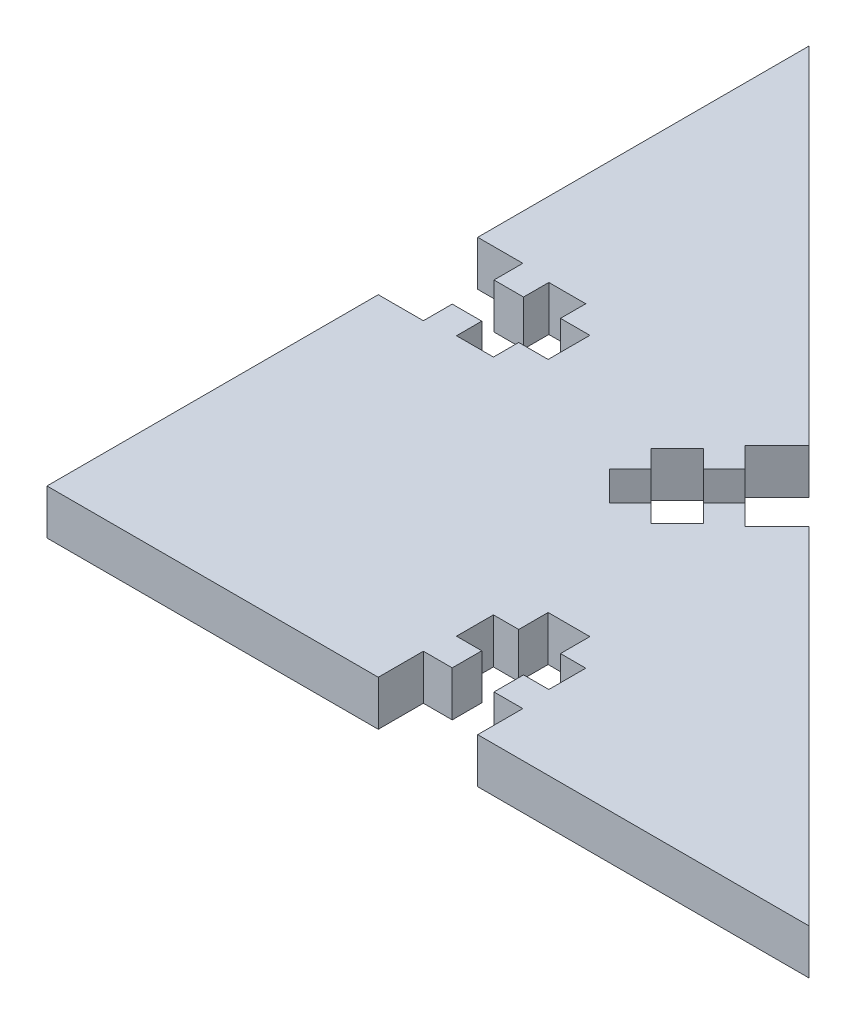
SolidWorks part; units mm, degrees
ref_plane "Front Plane" through (0, 0, 0) normal (0, 0, 1) x (1, 0, 0)
ref_plane "Top Plane" through (0, 0, 0) normal (0, 1, 0) x (1, 0, 0)
ref_plane "Right Plane" through (0, 0, 0) normal (1, 0, 0) x (0, 0, -1)
sketch "Sketch1" plane through (0, 0, 0) normal (0, 1, 0) x (1, 0, 0)
  line L0 (0, 0) -> (53.64, 0)
  line L1 (53.64, 0) -> (0, 53.64)
  line L2 (0, 53.64) -> (0, 0)
  dimension "D1" = 53.64
extrude "Boss-Extrude1" add sketch "Sketch1" along normal blind 3.175
sketch "Sketch2" plane through (0, 3.175, 0) normal (0, 1, 0) x (1, 0, 0)
  line L4 (0, 0) -> (53.64, 0) construction
  line L5 (23.32, 0) -> (30.32, 0)
  line L17 (23.32, 3.175) -> (23.32, 0)
  line L20 (23.32, 0) -> (30.32, 0)
  line L35 (23.32, 3.175) -> (25.35, 3.175)
  line L37 (30.32, 3.175) -> (30.32, 0)
  line L38 (0, 0) -> (26.82, 26.82) construction
  line L39 (53.64, 0) -> (0, 53.64) construction
  line L53 (25.35, 3.175) -> (25.35, 5.255)
  line L54 (23.57, 5.255) -> (25.35, 5.255)
  line L55 (23.57, 5.255) -> (23.57, 7.855)
  line L56 (23.57, 7.855) -> (25.35, 7.855)
  line L57 (25.35, 7.855) -> (25.35, 9.925)
  line L58 (25.35, 9.925) -> (28.29, 9.925)
  line L59 (28.29, 7.855) -> (28.29, 9.925)
  line L60 (28.29, 7.855) -> (30.07, 7.855)
  line L61 (30.07, 5.255) -> (30.07, 7.855)
  line L62 (28.29, 5.255) -> (30.07, 5.255)
  line L63 (28.29, 3.175) -> (28.29, 5.255)
  line L64 (28.29, 3.175) -> (30.32, 3.175)
  line L65 (26.82, 0) -> (26.82, 4.4623)
  line L85 (0, 26.82) -> (11.9124, 26.82) construction
  line L132 (0, 53.64) -> (0, 0) construction
  line L133 (29.2949, 24.3451) -> (27.0463, 22.0965)
  line L134 (27.0463, 22.0965) -> (25.6108, 23.532)
  line L135 (25.6108, 23.532) -> (24.1401, 22.0612)
  line L149 (24.1401, 22.0612) -> (25.3987, 20.8025)
  line L150 (25.3987, 20.8025) -> (23.5602, 18.964)
  line L151 (23.5602, 18.964) -> (22.3016, 20.2227)
  line L152 (22.3016, 20.2227) -> (20.8379, 18.759)
  line L153 (20.8379, 18.759) -> (18.759, 20.8379)
  line L154 (53.64, 0) -> (0, 53.64) construction
  line L155 (20.2227, 22.3016) -> (18.759, 20.8379)
  line L156 (18.964, 23.5602) -> (20.2227, 22.3016)
  line L157 (20.8025, 25.3987) -> (18.964, 23.5602)
  line L158 (22.0612, 24.1401) -> (20.8025, 25.3987)
  line L159 (23.532, 25.6108) -> (22.0612, 24.1401)
  line L160 (22.0965, 27.0463) -> (23.532, 25.6108)
  line L161 (24.3451, 29.2949) -> (22.0965, 27.0463)
  line L162 (29.2949, 24.3451) -> (24.3451, 29.2949)
  line L194 (0, 30.32) -> (3.175, 30.32)
  line L195 (0, 23.32) -> (0, 30.32)
  line L196 (0, 23.32) -> (3.175, 23.32)
  line L210 (3.175, 28.29) -> (3.175, 30.32)
  line L211 (3.175, 28.29) -> (5.255, 28.29)
  line L212 (5.255, 28.29) -> (5.255, 30.07)
  line L213 (5.255, 30.07) -> (7.855, 30.07)
  line L214 (7.855, 28.29) -> (7.855, 30.07)
  line L215 (7.855, 28.29) -> (9.925, 28.29)
  line L216 (9.925, 25.35) -> (9.925, 28.29)
  line L217 (7.855, 25.35) -> (9.925, 25.35)
  line L218 (7.855, 23.57) -> (7.855, 25.35)
  line L219 (5.255, 23.57) -> (7.855, 23.57)
  line L220 (5.255, 23.57) -> (5.255, 25.35)
  line L221 (3.175, 25.35) -> (5.255, 25.35)
  line L222 (3.175, 23.32) -> (3.175, 25.35)
  line L239 (-3.175, 28.29) -> (-5.255, 28.29) [skipped]
  line L240 (-3.175, 25.35) -> (-5.255, 25.35) [skipped]
  line L241 (-3.175, 23.32) -> (-3.175, 25.35) [skipped]
  line L242 (-5.255, 23.57) -> (-5.255, 25.35) [skipped]
  line L243 (-7.855, 23.57) -> (-7.855, 25.35) [skipped]
  line L244 (-9.925, 25.35) -> (-9.925, 28.29) [skipped]
  line L245 (-7.855, 25.35) -> (-9.925, 25.35) [skipped]
  line L246 (-5.255, 23.57) -> (-7.855, 23.57) [skipped]
  line L247 (-7.855, 28.29) -> (-9.925, 28.29) [skipped]
  line L248 (-7.855, 28.29) -> (-7.855, 30.07) [skipped]
  line L249 (-5.255, 28.29) -> (-5.255, 30.07) [skipped]
  line L250 (-3.175, 28.29) -> (-3.175, 30.32) [skipped]
  line L251 (-5.255, 30.07) -> (-7.855, 30.07) [skipped]
  line L252 (3.175, -30.32) -> (0, -30.32) [skipped]
  line L253 (0, -23.32) -> (0, -30.32) [skipped]
  line L254 (-25.35, -9.925) -> (-28.29, -9.925) [skipped]
  line L255 (-28.29, -7.855) -> (-28.29, -9.925) [skipped]
  line L256 (-28.29, -7.855) -> (-30.07, -7.855) [skipped]
  line L257 (-30.07, -5.255) -> (-30.07, -7.855) [skipped]
  line L258 (3.175, -23.32) -> (0, -23.32) [skipped]
  line L259 (3.175, -23.32) -> (3.175, -25.35) [skipped]
  line L260 (3.175, -25.35) -> (5.255, -25.35) [skipped]
  line L261 (5.255, -23.57) -> (5.255, -25.35) [skipped]
  line L262 (5.255, -23.57) -> (7.855, -23.57) [skipped]
  line L263 (7.855, -23.57) -> (7.855, -25.35) [skipped]
  line L264 (7.855, -25.35) -> (9.925, -25.35) [skipped]
  line L265 (9.925, -25.35) -> (9.925, -28.29) [skipped]
  line L266 (7.855, -28.29) -> (9.925, -28.29) [skipped]
  line L267 (7.855, -28.29) -> (7.855, -30.07) [skipped]
  line L268 (5.255, -30.07) -> (7.855, -30.07) [skipped]
  line L269 (5.255, -28.29) -> (5.255, -30.07) [skipped]
  line L270 (3.175, -28.29) -> (5.255, -28.29) [skipped]
  line L271 (3.175, -28.29) -> (3.175, -30.32) [skipped]
  line L272 (-30.32, -3.175) -> (-30.32, 0) [skipped]
  line L273 (-23.32, 0) -> (-30.32, 0) [skipped]
  line L274 (-23.32, -3.175) -> (-23.32, 0) [skipped]
  line L275 (-23.32, -3.175) -> (-25.35, -3.175) [skipped]
  line L276 (-25.35, -3.175) -> (-25.35, -5.255) [skipped]
  line L277 (-23.57, -5.255) -> (-25.35, -5.255) [skipped]
  line L278 (-23.57, -5.255) -> (-23.57, -7.855) [skipped]
  line L279 (-23.57, -7.855) -> (-25.35, -7.855) [skipped]
  line L280 (-25.35, -7.855) -> (-25.35, -9.925) [skipped]
  line L281 (-28.29, -5.255) -> (-30.07, -5.255) [skipped]
  line L282 (-28.29, -3.175) -> (-28.29, -5.255) [skipped]
  line L283 (-28.29, -3.175) -> (-30.32, -3.175) [skipped]
  point P63 (19.7984, 19.7984)
  point P99 (0, 0)
  line M99 (0, 53.64) -> (0, 0)
  line M101 (53.64, 0) -> (0, 53.64)
  dimension "D2" = 4
  dimension "D6" = 3.5
  dimension "D7" = 3.18
  dimension "D8" = 2.08
  dimension "D9" = 2.6
  dimension "D10" = 1.78
  dimension "D11" = 1.47
  dimension "D12" = 9.93
extrude "Cut-Extrude1" cut sketch "Sketch2" against normal blind 10 contours L161 L160 L159 L158 L157 L156 L155 L153 L152 L151 L150 L149 L135 L134 L133 M101 | L196 L222 L221 L220 L219 L218 L217 L216 L215 L214 L213 L212 L211 L210 L194 M99 | L37 L5 L17 L35 L53 L54 L55 L56 L57 L58 L59 L60 L61 L62 L63 L64
